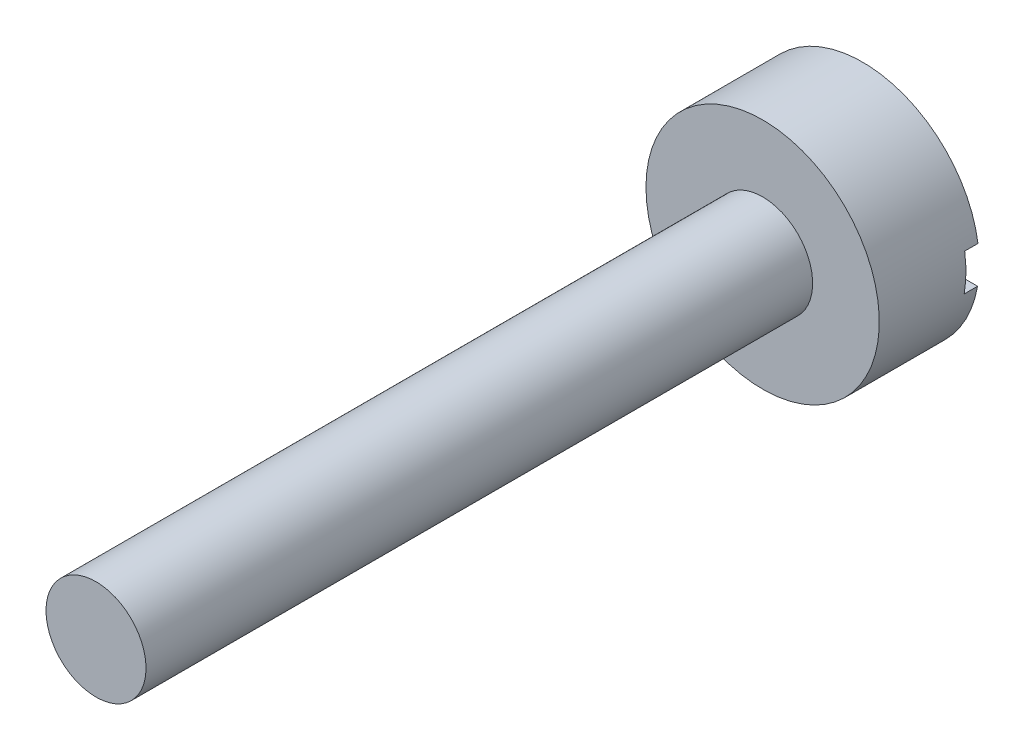
SolidWorks part; units mm, degrees
ref_plane "Front" through (0, 0, 0) normal (0, 0, 1) x (1, 0, 0)
ref_plane "Top" through (0, 0, 0) normal (0, 1, 0) x (1, 0, 0)
ref_plane "Right" through (0, 0, 0) normal (1, 0, 0) x (0, 0, -1)
sketch "Sketch2" plane through (0, 0, 0) normal (0, 1, 0) x (1, 0, 0)
  line L0 (0, 0) -> (1.905, 0)
  line L1 (1.905, 0) -> (1.905, 25.4)
  line L2 (1.905, 25.4) -> (4.445, 25.4)
  line L3 (4.445, 25.4) -> (4.445, 29.21)
  line L4 (4.445, 29.21) -> (0, 29.21)
  line L5 (0, 29.21) -> (0, 0)
  dimension "D1" = 1.905
  dimension "D2" = 25.4
  dimension "D3" = 2.54
  dimension "D4" = 3.81
revolve "Revolve1" add sketch "Sketch2" angle 360 about L5
sketch "Sketch3" plane through (0, 0, 0) normal (1, 0, 0) x (0, 0, -1)
  line L0 (0, 0) -> (29.21, 0) construction
  line L1 (29.21, -4.445) -> (29.21, 4.445) construction
  line L2 (29.21, 0.6577) -> (29.21, 0)
  line L3 (29.21, 0) -> (29.21, -0.762)
  line L4 (29.21, -0.762) -> (28.702, -0.762)
  line L5 (28.702, -0.762) -> (28.702, 0.6577)
  line L6 (28.702, 0.6577) -> (29.21, 0.6577)
  dimension "D1" = 0.6577
  dimension "D2" = 0.762
  dimension "D3" = 0.508
extrude "Cut-Extrude1" cut sketch "Sketch3" along normal mid plane 254 contours L6 L2 L3 L4 L5
